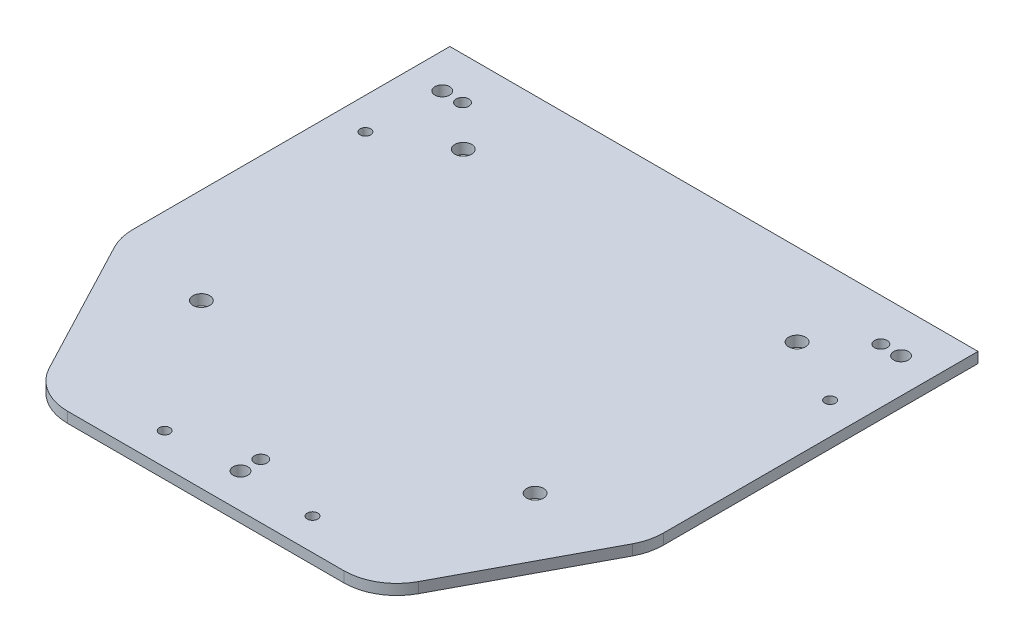
SolidWorks part; units mm, degrees
ref_plane "Plano frontal" through (0, 0, 0) normal (0, 0, 1) x (1, 0, 0)
ref_plane "Plano superior" through (0, 0, 0) normal (0, 1, 0) x (1, 0, 0)
ref_plane "Plano direito" through (0, 0, 0) normal (1, 0, 0) x (0, 0, -1)
sketch "Esboço1" plane through (0, 0, 0) normal (0, 1, 0) x (1, 0, 0)
  line L2 (399.2674, 124.203) -> (649.2674, 124.203)
  line L5 (649.2674, 124.203) -> (649.2674, 84.203)
  line L11 (646.3388, -36.4966) -> (611.2078, -102.538)
  line L12 (402.1324, -37.4447) -> (436.2433, -102.4178)
  line L14 (399.2674, 124.203) -> (399.2674, 84.203)
  line L16 (649.2674, 84.203) -> (649.2674, -24.7556)
  line L17 (399.2674, 84.203) -> (399.2674, -25.8239)
  line L18 (544.2674, -115.797) -> (589.1363, -115.797)
  line L19 (504.2674, -115.797) -> (458.3782, -115.797)
  line L23 (544.2674, -115.797) -> (504.2674, -115.797)
  arc A0 (399.2674, -25.8239) -> (402.1324, -37.4447) centre (424.2674, -25.8239) ccw
  arc A1 (436.2433, -102.4178) -> (458.3782, -115.797) centre (458.3782, -90.797) ccw
  arc A2 (589.1363, -115.797) -> (611.2078, -102.538) centre (589.1363, -90.797) ccw
  arc A3 (646.3388, -36.4966) -> (649.2674, -24.7556) centre (624.2674, -24.7556) ccw
  dimension "D4" = 40
  dimension "D5" = 40
  dimension "D6" = 25
  dimension "D16" = 40
  dimension "D2" = 250
extrude "Ressalto-extrusão4" add sketch "Esboço1" along normal blind 5
sketch "Esboço2" plane through (0, 5, 0) normal (0, 1, 0) x (1, 0, 0)
  line L0 (399.2674, 124.203) -> (649.2674, 124.203) construction
  line L1 (589.1363, -115.797) -> (458.3782, -115.797) construction
  line L3 (414.2674, 69.203) -> (399.2674, 69.203) construction
  line L6 (559.2674, -115.797) -> (559.2674, -100.797) construction
  line L11 (489.2674, -100.797) -> (489.2674, -115.797) construction
  line L13 (649.2674, 69.203) -> (634.2674, 69.203) construction
  circle A0 centre (559.2674, -100.797) radius 2.5
  circle A1 centre (489.2674, -100.797) radius 2.5
  circle A2 centre (634.2674, 69.203) radius 2.5
  circle A3 centre (414.2674, 69.203) radius 2.5
  dimension "D1" = 15
  dimension "D6" = 70
  dimension "D2" = 55
  dimension "D3" = 55
  dimension "D4" = 15
  dimension "D5" = 15
  dimension "D8" = 15
extrude "Corte-extrusão1" cut sketch "Esboço2" against normal blind 5
sketch "Esboço3" plane through (0, 5, 0) normal (0, 1, 0) x (1, 0, 0)
  circle A7 centre (602.5953, 85.2233) radius 4
  circle A8 centre (444.5953, 85.2233) radius 4
  circle A9 centre (602.5953, -38.7767) radius 4
  circle A10 centre (444.5953, -38.7767) radius 4
  dimension "D1" = 158
  dimension "D2" = 158
  dimension "D3" = 124
  dimension "D4" = 124
extrude "Corte-extrusão2" cut sketch "Esboço3" against normal blind 5
sketch "Esboço4" plane through (0, 5, 0) normal (0, 1, 0) x (1, 0, 0)
  line L0 (523.7573, -115.797) -> (523.7573, -99.397) construction
  line L2 (589.1363, -115.797) -> (458.3782, -115.797) construction
  line L3 (649.2674, 124.203) -> (649.2674, 104.203) construction
  line L4 (649.2674, 124.203) -> (649.2674, -24.7556) construction
  line L5 (649.2674, 104.203) -> (399.2674, 104.203) construction
  line L6 (399.2674, 124.203) -> (399.2674, -25.8239) construction
  line L7 (649.2674, 104.203) -> (632.8674, 104.203) construction
  line L8 (399.2674, 104.203) -> (415.6674, 104.203) construction
  line L9 (649.2674, 104.203) -> (623.2674, 104.203) construction
  line L10 (399.2674, 104.203) -> (425.2674, 104.203) construction
  line L11 (523.7573, -115.797) -> (523.7573, -89.797) construction
  circle A1 centre (523.7573, -99.397) radius 3.5
  circle A2 centre (632.8674, 104.203) radius 3.5
  circle A3 centre (415.6674, 104.203) radius 3.5
  circle A4 centre (623.2674, 104.203) radius 3
  circle A5 centre (425.2674, 104.203) radius 3
  circle A6 centre (523.7573, -89.797) radius 3
  dimension "D1" = 7
extrude "Corte-extrusão3" cut sketch "Esboço4" against normal blind 10
